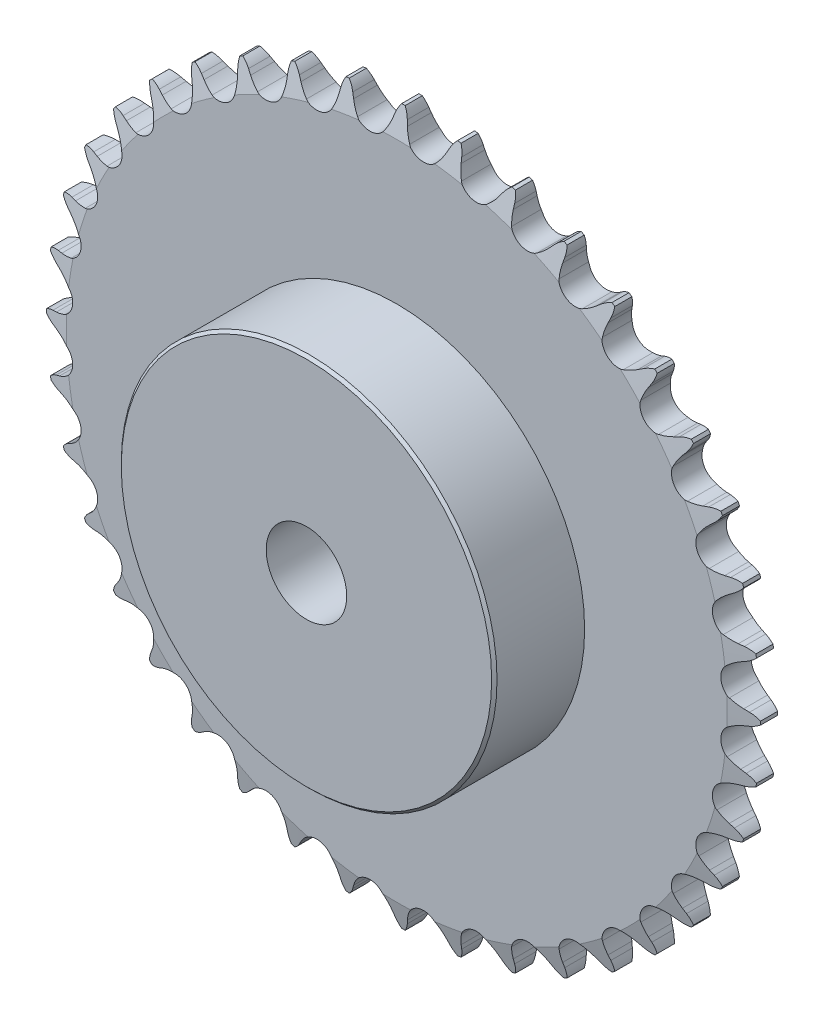
SolidWorks part; units mm, degrees
ref_plane "Front Plane" through (0, 0, 0) normal (0, 0, 1) x (1, 0, 0)
ref_plane "Top Plane" through (0, 0, 0) normal (0, 1, 0) x (1, 0, 0)
ref_plane "Right Plane" through (0, 0, 0) normal (1, 0, 0) x (0, 0, -1)
sketch "Sketch0" plane through (0, 0, 0) normal (0, 0, 1) x (1, 0, 0)
  line L0 (6.35, -80.6844) -> (0, 0) construction
  line L1 (0, 0) -> (18.8936, -78.6977) construction
  line L2 (0, 0) -> (-6.35, -80.6844) construction
  line L3 (6.35, -80.6844) -> (18.8936, -78.6977) construction
  line L4 (6.35, -80.6844) -> (-6.35, -80.6844) construction
  line L5 (11.469, -81.5976) -> (11.0001, -80.5639)
  line L6 (6.35, -80.6844) -> (0, -81.1842) construction
  line L7 (1.4369, -82.3871) -> (1.7383, -81.2928)
  line L8 (0, -80.6844) -> (0, -84.4944) construction
  line L9 (9.3842, -78.0468) -> (1.5653, -84.8437) construction
  line L10 (0, 0) -> (0, -80.6844) construction
  line L11 (11.0001, -80.5639) -> (1.5653, -84.8437) construction
  line L12 (0, -84.4944) -> (0, -84.9971) construction
  line L13 (17.3081, -78.9488) -> (11.469, -81.5976) construction
  circle A0 centre (0, 0) radius 84.4944 construction
  circle A1 centre (0, 0) radius 80.9339 construction
  arc A2 (-5.1211, -87.0852) -> (18.6812, -85.2119) centre (0, 0) ccw
  circle A3 centre (0, 0) radius 84.9971 construction
  circle A4 centre (6.35, -80.6844) radius 3.9624 construction
  arc A7 (9.3842, -78.0468) -> (2.9406, -78.554) centre (6.35, -80.6844) ccw
  circle A8 centre (6.35, -80.6844) radius 4.0203 construction
  arc A9 (11.469, -81.5976) -> (18.6812, -85.2119) centre (17.3081, -78.9488) ccw
  arc A10 (11.0001, -80.5639) -> (9.3842, -78.0468) centre (1.5653, -84.8437) ccw
  arc A11 (1.4369, -82.3871) -> (-5.1211, -87.0852) centre (-4.7447, -80.6844) cw
  arc A12 (1.7383, -81.2928) -> (2.9406, -78.554) centre (11.7265, -84.044) cw
  dimension "D1" = 4.0203
  dimension "R" = 4.0203
sketch "Sketch1" plane through (0, 0, 0) normal (1, 0, 0) x (0, 0, -1)
  line L0 (3.6068, 0) -> (-3.6068, 0)
  line L1 (-3.6068, 0) -> (-3.6068, 78.1444)
  line L2 (-3.6068, 78.1444) -> (-2.0193, 84.4944)
  line L3 (-2.0193, 84.4944) -> (2.0193, 84.4944)
  line L4 (2.0193, 84.4944) -> (3.6068, 78.1444)
  line L5 (3.6068, 78.1444) -> (3.6068, 0)
  line L7 (0, 84.4944) -> (0, 0) construction
  line L8 (-3.6068, 78.1444) -> (3.6068, 78.1444) construction
  line L9 (0, 84.4944) -> (0, -84.4944) construction
  line L10 (-3.6068, 78.1444) -> (-3.6068, 84.4944) construction
  line L11 (-3.6068, 84.4944) -> (-2.0193, 84.4944) construction
  line L12 (2.0193, 84.4944) -> (3.6068, 84.4944) construction
  line L13 (3.6068, 84.4944) -> (3.6068, 78.1444) construction
  line L14 (0, 0) -> (-6.4008, 0) construction
  line L22 (3.6068, 0) -> (-24.9682, 0) construction
  line L24 (-3.6068, 0) -> (-3.6068, 73.9534) construction
revolve "Revolve1" add sketch "Sketch1" angle 360 mid plane about L0
extrude "Cut-Extrude1" cut sketch "Sketch0" against normal through all and the other way through all
pattern_circular "CirPattern1" count 40 over 360 about axis through (0, 0, 0) along (0, 0, 1) of "Cut-Extrude1"
sketch "Sketch2" plane through (0, 0, 0) normal (0, 0, 1) x (1, 0, 0)
  circle A0 centre (0, 0) radius 9.525 construction
  circle A1 centre (0, 0) radius 44.45
  circle A2 centre (0, 0) radius 84.455 construction
  dimension "Bore" = 19.05
  dimension "Hub Dia." = 88.9
  dimension "OD" = 168.91
extrude "Boss-Extrude1" add sketch "Sketch2" along normal up to vertex (24.9682 mm away) from surface at 3.6068 starting at face at (0, 0, 3.6068)
sketch "Sketch3" plane through (0, 0, 0) normal (0, 0, 1) x (1, 0, 0)
  circle A0 centre (0, 0) radius 9.525 construction
  circle A1 centre (0, 0) radius 9.525
extrude "Cut-Extrude2" cut sketch "Sketch3" along normal through all and the other way through all
sketch "Sketch4" plane through (0, 0, 0) normal (1, 0, 0) x (0, 0, -1)
  line L0 (-24.9682, 44.45) -> (-24.9682, 43.815)
  line L1 (-3.6068, 84.4944) -> (-9.017, 84.4944)
  line L2 (-3.6068, 84.4944) -> (-3.6068, 73.9534)
  line L3 (-3.6068, 73.9534) -> (-9.017, 73.9534)
  line L4 (-9.017, 84.4944) -> (-9.017, 73.9534)
  line L9 (-24.9682, 43.815) -> (-24.3332, 44.45)
  line L10 (-24.3332, 44.45) -> (-24.9682, 44.45)
  dimension "C" = 0.635
  dimension "D3" = 5.4102
revolve "Cut-Revolve1" cut sketch "Sketch4" angle 360 mid plane about L22
equation "\"360/N@Sketch0\" = 360/\"Teeth@CirPattern1\""
equation "\"Ds@Sketch0\" = 1.005 * \"Dr@Sketch0\" + 0.003"
equation "\"R@Sketch0\" = 1/2 * \"Ds@Sketch0\""
equation "\"A@Sketch0\" = 35 +  ( 60 / \"Teeth@CirPattern1\" ) "
equation "\"B@Sketch0\" = 18 -  ( 56 / \"Teeth@CirPattern1\" )"
equation "\"ac@Sketch0\" = 0.8 * \"Dr@Sketch0\""
equation "\"ab@Sketch0\" = 1.4 * \"Dr@Sketch0\""
equation "\"J@Sketch0\" = 0.3 * \"Pitch@Sketch0\""
equation "\"h@Sketch1\" = \"Pitch@Sketch0\" / 2"
equation "\"g@Sketch1\" = \"h@Sketch1\" / 4"
equation "\"MHD@Sketch1\" = \"Pitch@Sketch0\" * ( cotan ( 180 / \"Teeth@CirPattern1\" ) - 1 ) - 0.030"
equation "\"D3@Sketch4\" = \"t@Sketch1\" * 3 / 4"
